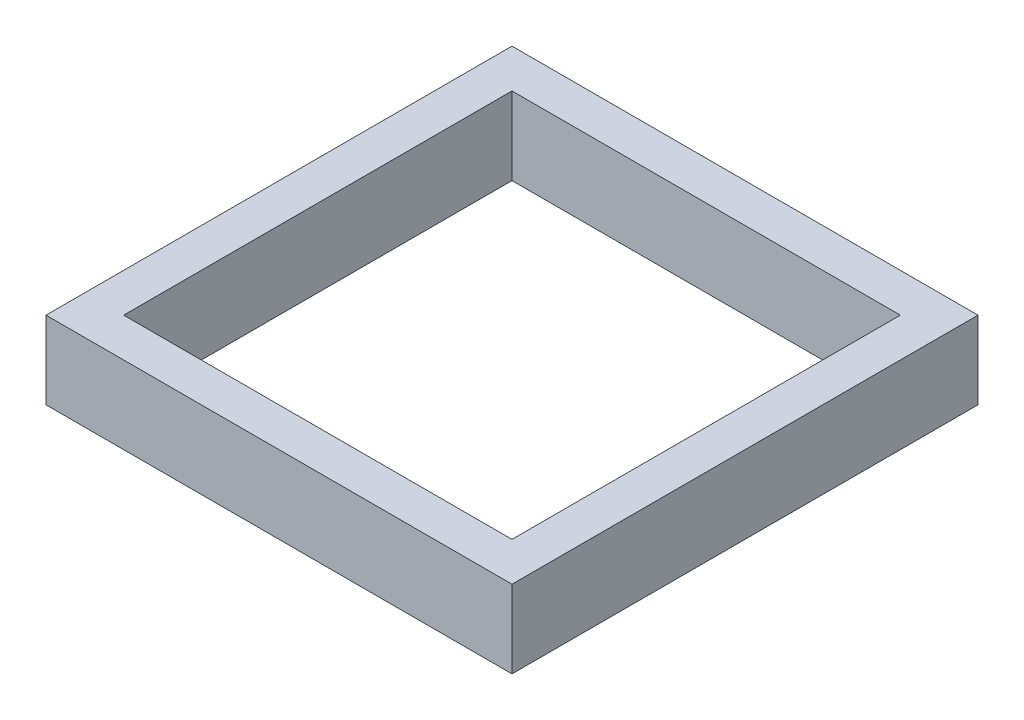
SolidWorks part; units mm, degrees
ref_plane "Front Plane" through (0, 0, 0) normal (0, 0, 1) x (1, 0, 0)
ref_plane "Top Plane" through (0, 0, 0) normal (0, 1, 0) x (1, 0, 0)
ref_plane "Right Plane" through (0, 0, 0) normal (1, 0, 0) x (0, 0, -1)
sketch "Sketch1" plane through (0, 0, 0) normal (0, 1, 0) x (1, 0, 0)
  line L1 (30, -30) -> (-30, -30)
  line L2 (30, -30) -> (30, 30)
  line L3 (30, 30) -> (-30, 30)
  line L4 (-30, -30) -> (-30, 30)
  line L5 (30, -30) -> (-30, 30) construction
  line L6 (30, 30) -> (-30, -30) construction
  point P0 (0, 0)
  dimension "D1" = 60
  dimension "D2" = 60
extrude "Boss-Extrude1" add sketch "Sketch1" along normal blind 10
sketch "Sketch2" plane through (0, 10, 0) normal (0, 1, 0) x (1, 0, 0)
  line L1 (25, -25) -> (-25, -25)
  line L2 (25, -25) -> (25, 25)
  line L3 (25, 25) -> (-25, 25)
  line L4 (-25, -25) -> (-25, 25)
  line L5 (25, -25) -> (-25, 25) construction
  line L6 (25, 25) -> (-25, -25) construction
  point P0 (0, 0)
  dimension "D1" = 50
  dimension "D2" = 50
extrude "Cut-Extrude1" cut sketch "Sketch2" against normal blind 10
